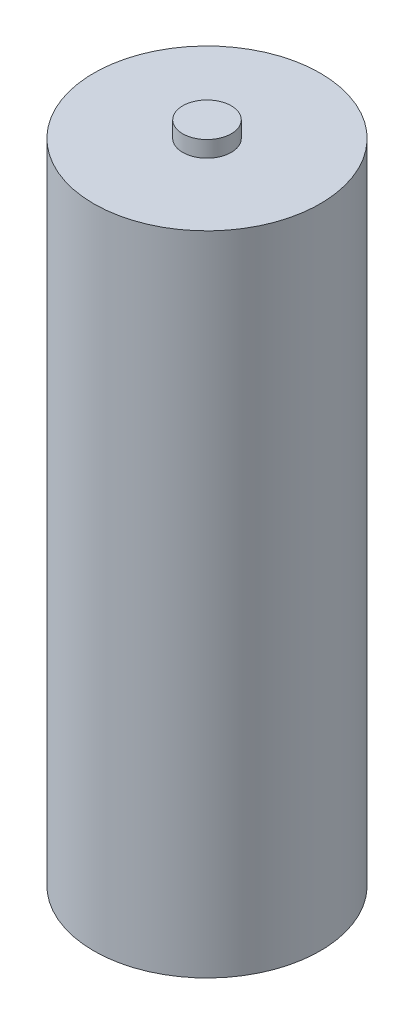
SolidWorks part; units mm, degrees
ref_plane "Front Plane" through (0, 0, 0) normal (0, 0, 1) x (1, 0, 0)
ref_plane "Top Plane" through (0, 0, 0) normal (0, 1, 0) x (1, 0, 0)
ref_plane "Right Plane" through (0, 0, 0) normal (1, 0, 0) x (0, 0, -1)
sketch "Sketch1" plane through (0, 0, 0) normal (0, 1, 0) x (1, 0, 0)
  circle A0 centre (0, 0) radius 7
  dimension "D1" = 14
extrude "Boss-Extrude1" add sketch "Sketch1" along normal blind 40
sketch "Sketch2" plane through (0, 40, 0) normal (0, 1, 0) x (1, 0, 0)
  circle A0 centre (0, 0) radius 1.5
  dimension "D1" = 3
extrude "Boss-Extrude2" add sketch "Sketch2" along normal blind 1
